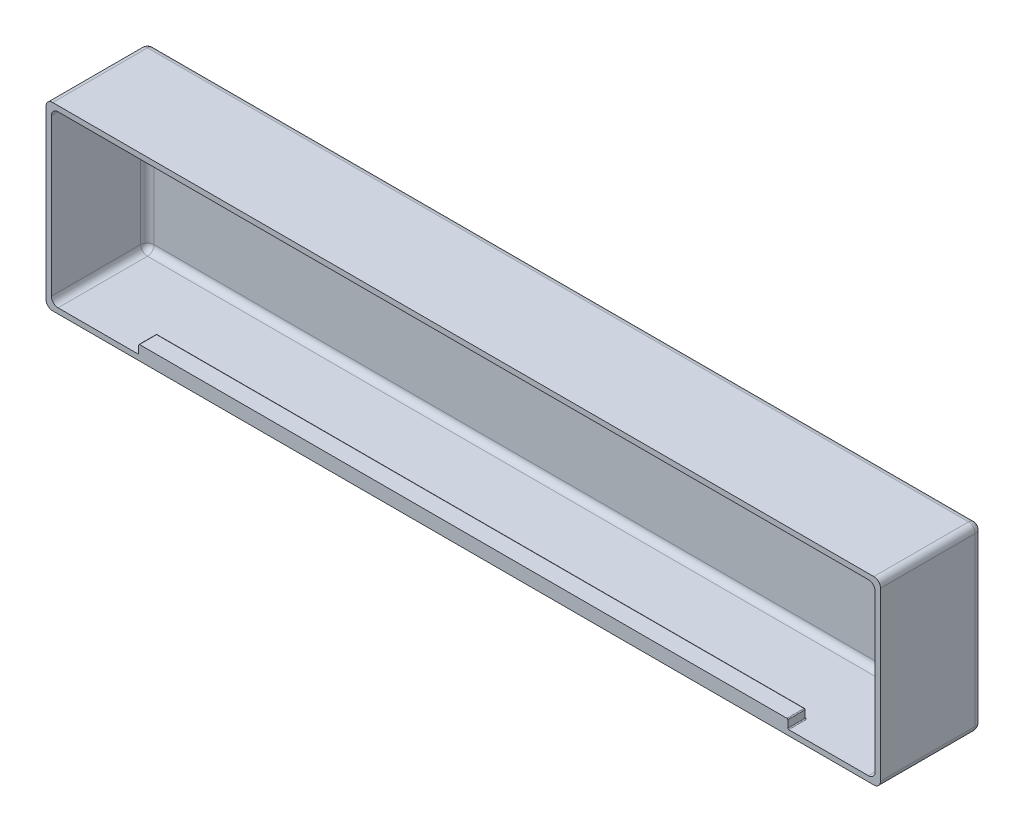
SolidWorks part; units mm, degrees
material "NEOPRENE"
ref_plane "Front" through (0, 0, 0) normal (0, 0, 1) x (1, 0, 0)
ref_plane "Top" through (0, 0, 0) normal (0, 1, 0) x (1, 0, 0)
ref_plane "Right" through (0, 0, 0) normal (1, 0, 0) x (0, 0, -1)
sketch "Sketch1" plane through (0, 0, 0) normal (0, 0, 1) x (1, 0, 0)
  line L1 (-118.618, -25.654) -> (118.618, -25.654)
  line L2 (-118.618, -25.654) -> (-118.618, 25.654)
  line L3 (-118.618, 25.654) -> (118.618, 25.654)
  line L4 (118.618, -25.654) -> (118.618, 25.654)
  line L5 (-118.618, -25.654) -> (118.618, 25.654) construction
  line L6 (-118.618, 25.654) -> (118.618, -25.654) construction
  point P0 (0, 0)
  dimension "D1" = 51.308
  dimension "D2" = 237.236
extrude "Boss-Extrude1" add sketch "Sketch1" along normal blind 28.829
shell "Shell1" thickness 1.524
fillet "Fillet1" radius 1.905 8 edges at (0, -24.13, 1.524) (-117.094, 0, 1.524) (0, 24.13, 1.524) (117.094, 0, 1.524) (117.094, -24.13, 15.1765) (117.094, 24.13, 15.1765) (-117.094, -24.13, 15.1765) (-117.094, 24.13, 15.1765)
fillet "Fillet2" radius 1.905 8 edges at (118.618, 0, 0) (-118.618, 0, 0) (0, 25.654, 0) (-118.618, 25.654, 14.4145) (-118.618, -25.654, 14.4145) (0, -25.654, 0) (118.618, -25.654, 14.4145) (118.618, 25.654, 14.4145)
sketch "Sketch2" plane through (0, 0, 0) normal (0, 0, -1) x (-1, 0, 0)
  circle A0 centre (-45.2, 2.46) radius 4.826
  circle A1 centre (45, 2.46) radius 4.826
  dimension "D1" = 9.652
extrude "Cut-Extrude1" cut sketch "Sketch2" against normal blind 2.54
sketch "Sketch3" plane through (0, -24.13, 0) normal (0, 1, 0) x (1, 0, 0)
  line L0 (0, -28.829) -> (0, 0) construction
  line L1 (-115.189, -28.829) -> (115.189, -28.829) construction
  line L3 (92.2655, -23.749) -> (-92.2655, -23.749)
  line L4 (92.2655, -23.749) -> (92.2655, -28.829)
  line L5 (92.2655, -28.829) -> (-92.2655, -28.829)
  line L6 (-92.2655, -23.749) -> (-92.2655, -28.829)
  line L7 (92.2655, -23.749) -> (-92.2655, -28.829) construction
  line L8 (92.2655, -28.829) -> (-92.2655, -23.749) construction
  point P5 (0, -26.289)
  dimension "D1" = 5.08
  dimension "D2" = 184.531
extrude "Boss-Extrude2" add sketch "Sketch3" along normal blind 2.54
fillet "Fillet3" radius 0.254 8 edges at (-92.2655, -22.86, 23.749) (-92.2655, -21.59, 26.289) (0, -21.59, 23.749) (92.2655, -21.59, 26.289) (92.2655, -24.13, 26.289) (-92.2655, -24.13, 26.289) (0, -24.13, 23.749) (92.2655, -22.86, 23.749)
sketch "Sketch4" [suppressed] plane through (0, 0, 0) normal (0, 0, -1) x (-1, 0, 0)
  line L0 (91.694, -5.9943) -> (59.8424, 12.3952) construction
  circle A0 centre (75.7682, 3.2005) radius 10.795
  dimension "D1" = 21.59
extrude "Cut-Extrude2" [suppressed] cut sketch "Sketch4" against normal blind 2.54
